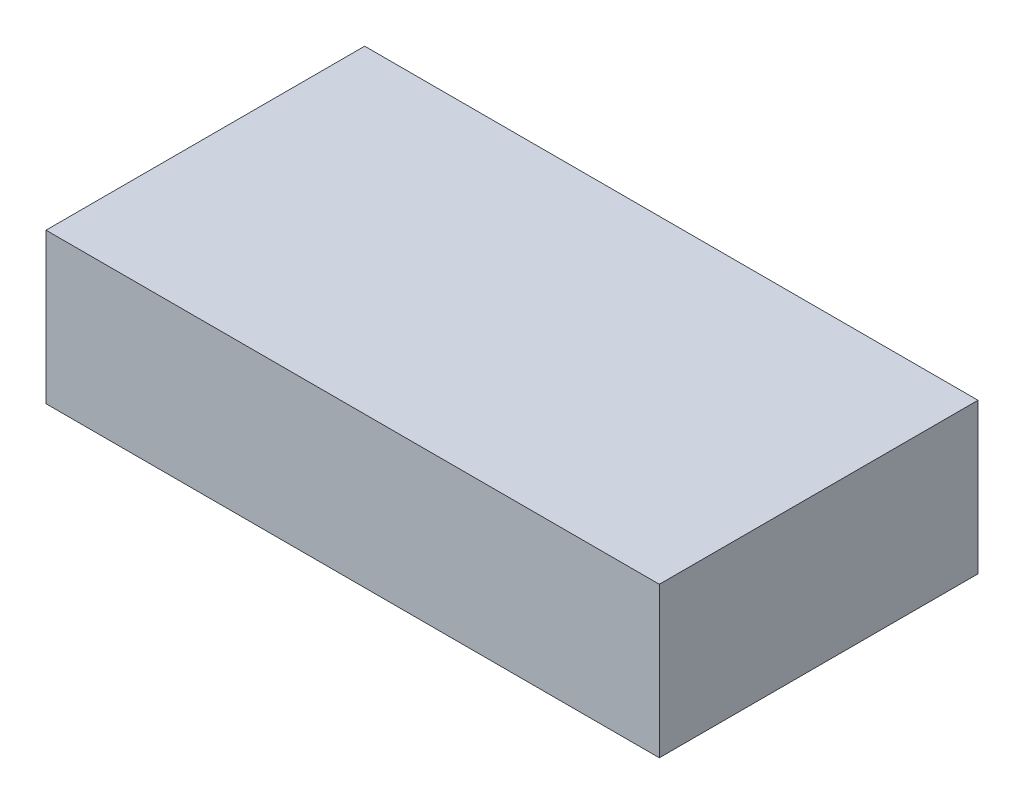
SolidWorks part; units mm, degrees
ref_plane "Front Plane" through (0, 0, 0) normal (0, 0, 1) x (1, 0, 0)
ref_plane "Top Plane" through (0, 0, 0) normal (0, 1, 0) x (1, 0, 0)
ref_plane "Right Plane" through (0, 0, 0) normal (1, 0, 0) x (0, 0, -1)
sketch "Sketch1" plane through (0, 0, 0) normal (0, 1, 0) x (1, 0, 0)
  line L1 (-51, -26.5) -> (51, -26.5)
  line L2 (-51, -26.5) -> (-51, 26.5)
  line L3 (-51, 26.5) -> (51, 26.5)
  line L4 (51, -26.5) -> (51, 26.5)
  line L5 (-51, -26.5) -> (51, 26.5) construction
  line L6 (-51, 26.5) -> (51, -26.5) construction
  point P0 (0, 0)
  dimension "D1" = 102
  dimension "D2" = 53
extrude "Boss-Extrude1" add sketch "Sketch1" along normal blind 25
